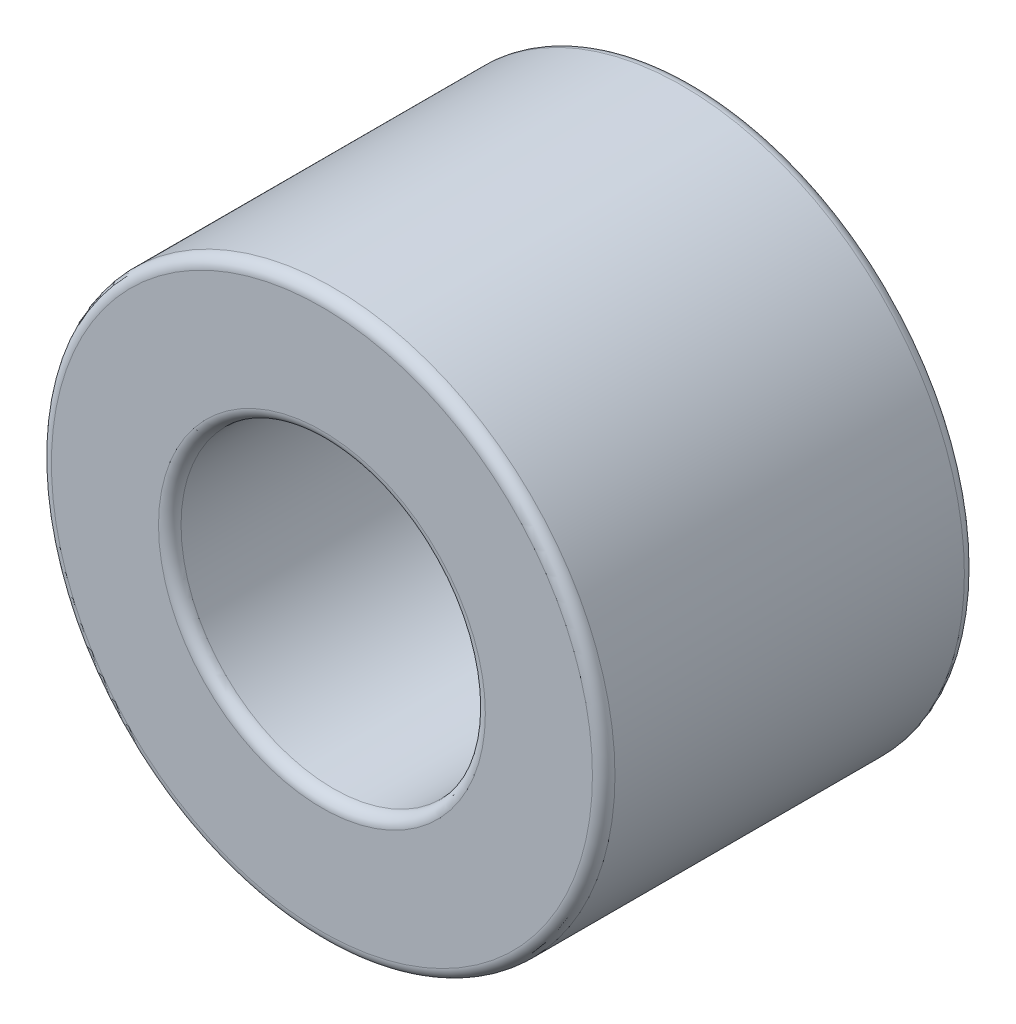
SolidWorks part; units mm, degrees
ref_plane "Front" through (0, 0, 0) normal (0, 0, 1) x (1, 0, 0)
ref_plane "Top" through (0, 0, 0) normal (0, 1, 0) x (1, 0, 0)
ref_plane "Right" through (0, 0, 0) normal (1, 0, 0) x (0, 0, -1)
sketch "Sketch1" plane through (0, 0, 0) normal (0, 0, 1) x (1, 0, 0)
  circle A0 centre (0, 0) radius 1.7145
  circle A1 centre (0, 0) radius 3.175
  dimension "D1" = 3.429
  dimension "D2" = 6.35
extrude "Boss-Extrude1" add sketch "Sketch1" along normal blind 4.191
fillet "Fillet1" radius 0.127 4 edges at (1.7145, 0, 0) (3.175, 0, 0) (3.175, 0, 4.191) (1.7145, 0, 4.191)
